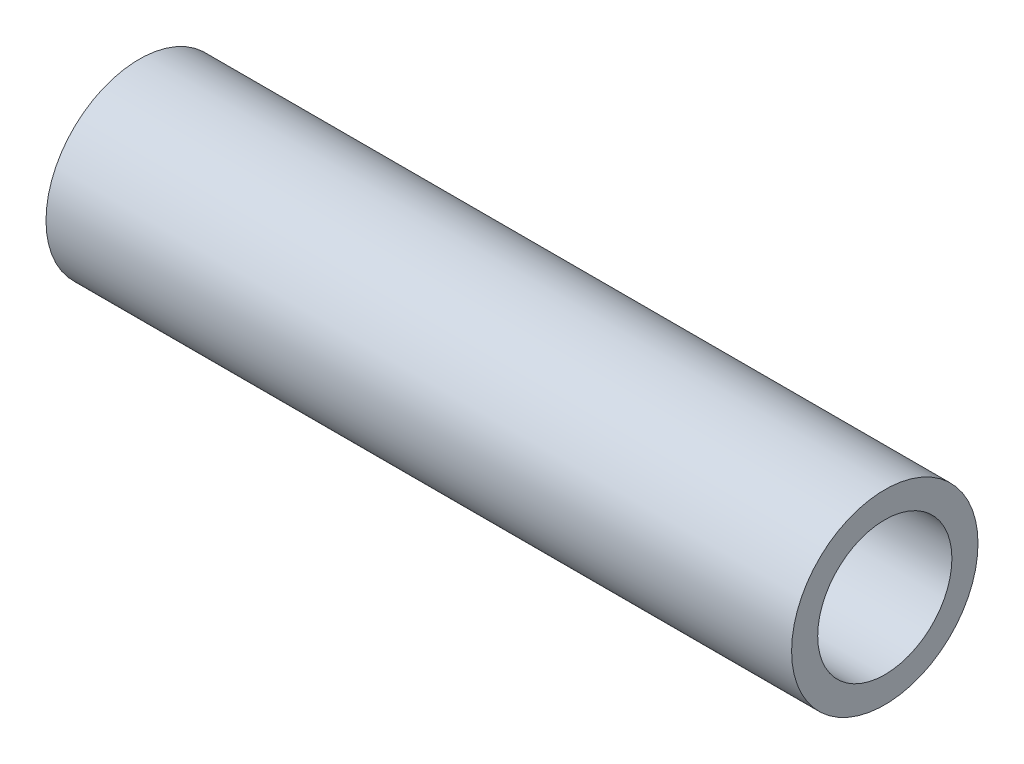
SolidWorks part; units mm, degrees
ref_plane "前视基准面" through (0, 0, 0) normal (0, 0, 1) x (1, 0, 0)
ref_plane "上视基准面" through (0, 0, 0) normal (0, 1, 0) x (1, 0, 0)
ref_plane "右视基准面" through (0, 0, 0) normal (1, 0, 0) x (0, 0, -1)
other "Configuration Table"
sketch "草图4" plane through (0, 0, 0) normal (1, 0, 0) x (0, 0, -1)
  circle A0 centre (0, 0) radius 2.5
  dimension "D1" = 5
extrude "凸台-拉伸1" add sketch "草图4" along normal blind 20
sketch "草图5" plane through (0, 0, 0) normal (-1, 0, 0) x (0, 0, 1)
  circle A0 centre (0, 0) radius 1.8
  circle A1 centre (0, 0) radius 2.5 construction
  dimension "D1" = 0.7
extrude "切除-拉伸2" cut sketch "草图5" against normal up to surface (20 mm away) up to face at (20, 0, -2.5)
